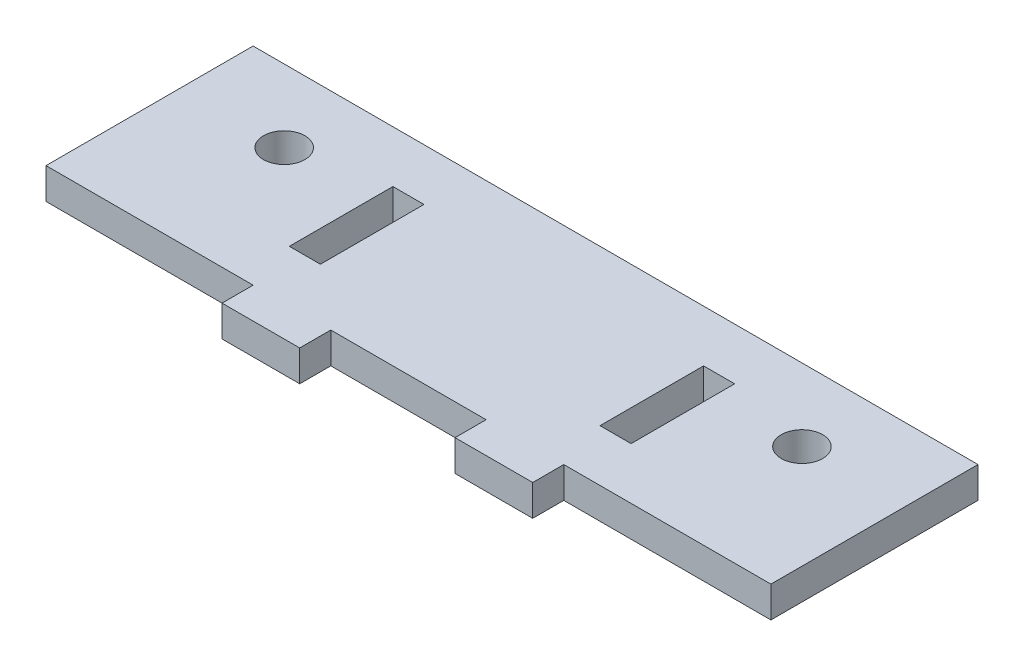
SolidWorks part; units mm, degrees
ref_plane "Front Plane" through (0, 0, 0) normal (0, 0, 1) x (1, 0, 0)
ref_plane "Top Plane" through (0, 0, 0) normal (0, 1, 0) x (1, 0, 0)
ref_plane "Right Plane" through (0, 0, 0) normal (1, 0, 0) x (0, 0, -1)
sketch "Sketch1" plane through (0, 0, 0) normal (0, 1, 0) x (1, 0, 0)
  line L0 (20, 20) -> (20, 0) construction
  line L1 (0, 0) -> (20, 0)
  line L2 (0, 0) -> (0, 20)
  line L3 (0, 20) -> (70, 20)
  line L4 (70, 0) -> (70, 20)
  line L5 (50, 20) -> (50, 0) construction
  line L6 (35, 20) -> (35, 0) construction
  line L7 (18.5, 15) -> (21.5, 15)
  line L8 (18.5, 15) -> (18.5, 5)
  line L9 (18.5, 5) -> (21.5, 5)
  line L10 (21.5, 15) -> (21.5, 5)
  line L11 (51.5, 5) -> (48.5, 5)
  line L12 (48.5, 15) -> (48.5, 5)
  line L13 (51.5, 15) -> (51.5, 5)
  line L14 (51.5, 15) -> (48.5, 15)
  line L15 (10, 20) -> (10, 0) construction
  line L16 (50, -3) -> (42.5, -3)
  line L17 (27.5, 0) -> (27.5, 20) construction
  line L18 (42.5, 0) -> (42.5, -3)
  line L20 (20, 0) -> (20, -3)
  line L21 (20, -3) -> (27.5, -3)
  line L22 (27.5, 0) -> (27.5, -3)
  line L24 (50, 0) -> (50, -3)
  line L25 (27.5, 0) -> (42.5, 0)
  line L26 (50, 0) -> (70, 0)
  circle A0 centre (10, 13) radius 2
  circle A2 centre (60, 13) radius 2
  point P28 (0, 0)
  point P31 (-5.2691, 17.0196)
  point P32 (-5.4348, 21.7006)
  dimension "D10" = 7.5
  dimension "D11" = 3
  dimension "D13" = 4
  dimension "D1" = 70
  dimension "D2" = 20
  dimension "D3" = 20
  dimension "D5" = 3
  dimension "D6" = 10
  dimension "D7" = 1.5
  dimension "D8" = 5
  dimension "D9" = 10
extrude "Boss-Extrude1" add sketch "Sketch1" along normal blind 3
